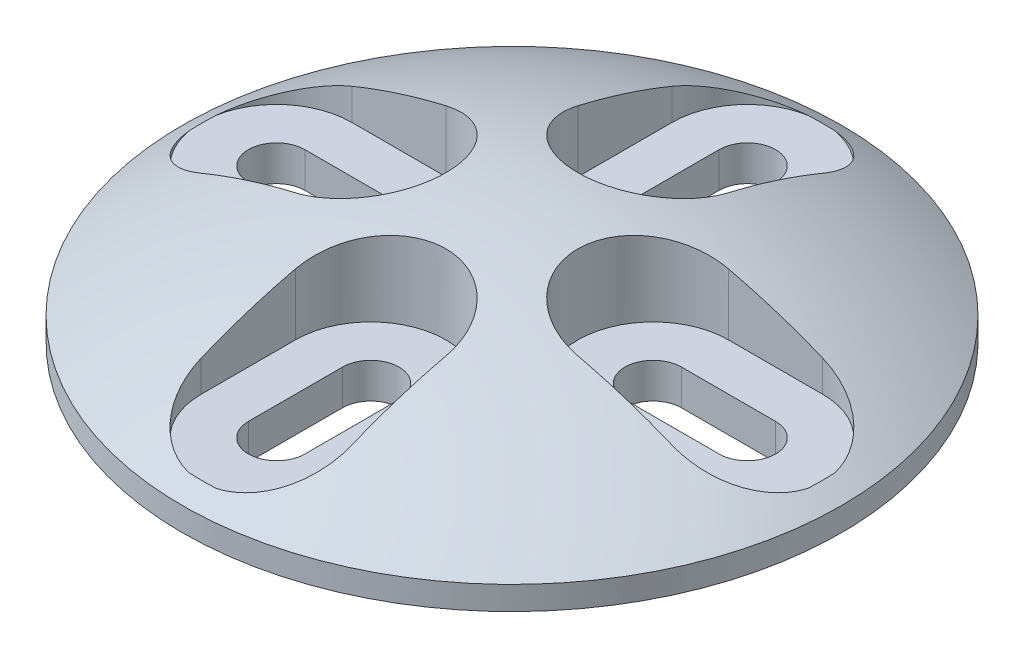
SolidWorks part; units mm, degrees
ref_plane "Front Plane" through (0, 0, 0) normal (0, 0, 1) x (1, 0, 0)
ref_plane "Top Plane" through (0, 0, 0) normal (0, 1, 0) x (1, 0, 0)
ref_plane "Right Plane" through (0, 0, 0) normal (1, 0, 0) x (0, 0, -1)
sketch "Sketch1" plane through (0, 0, 0) normal (0, 0, 1) x (1, 0, 0)
  line L0 (0, 0) -> (-14, 0)
  line L1 (0, 0) -> (0, 5)
  line L2 (-14, 0) -> (-14, 1)
  arc A0 (0, 5) -> (-14, 1) centre (0, -21.5) ccw
  dimension "D3" = 1
  dimension "D1" = 14
  dimension "D2" = 5
revolve "Revolve1" add sketch "Sketch1" angle 360 about L1
ref_plane "Plane1" through (0, 5, 0) normal (0, 1, 0) x (1, 0, 0)
sketch "Sketch2" plane through (0, 5, 0) normal (0, 1, 0) x (1, 0, 0)
  line L0 (0, 0) -> (0, -50000) construction
  line L1 (0, 0) -> (-50000, 0) construction
  line L2 (0, 10) -> (0, 6) construction
  line L3 (1.2, 10) -> (1.2, 6)
  line L4 (-1.2, 10) -> (-1.2, 6)
  line L5 (10, 0) -> (6, 0) construction
  line L6 (10, -1.2) -> (6, -1.2)
  line L7 (10, 1.2) -> (6, 1.2)
  line L8 (0, -10) -> (0, -6) construction
  line L9 (-1.2, -10) -> (-1.2, -6)
  line L10 (1.2, -10) -> (1.2, -6)
  line L11 (-10, 0) -> (-6, 0) construction
  line L12 (-10, 1.2) -> (-6, 1.2)
  line L13 (-10, -1.2) -> (-6, -1.2)
  arc A0 (1.2, 10) -> (-1.2, 10) centre (0, 10) ccw
  arc A1 (-1.2, 6) -> (1.2, 6) centre (0, 6) ccw
  arc A2 (10, -1.2) -> (10, 1.2) centre (10, 0) ccw
  arc A3 (6, 1.2) -> (6, -1.2) centre (6, 0) ccw
  arc A4 (-1.2, -10) -> (1.2, -10) centre (0, -10) ccw
  arc A5 (1.2, -6) -> (-1.2, -6) centre (0, -6) ccw
  arc A6 (-10, 1.2) -> (-10, -1.2) centre (-10, 0) ccw
  arc A7 (-6, -1.2) -> (-6, 1.2) centre (-6, 0) ccw
  point P7 (0, 8)
  point P17 (8, 0)
  point P24 (0, -8)
  point P31 (-8, 0)
  point P36 (0, 0)
  dimension "D1" = 4
  dimension "D2" = 2.4
  dimension "D3" = 8
  dimension "D4" = 4
extrude "Cut-Extrude1" cut sketch "Sketch2" against normal through all
sketch "Sketch3" plane through (0, 5, 0) normal (0, 1, 0) x (1, 0, 0)
  line L9 (10.0018, 3.1974) -> (6.0018, 3.1974)
  line L10 (6.0018, -3.2026) -> (10.0018, -3.2026)
  line L11 (3.2, 6) -> (3.2, 10)
  line L12 (-3.2, 10) -> (-3.2, 6)
  line L13 (3.2, 6) -> (3.2, 10)
  line L16 (-3.2, 10) -> (-3.2, 6)
  line L17 (3.1992, -10.0044) -> (3.1992, -6.0044)
  line L18 (-3.2008, -6.0044) -> (-3.2008, -10.0044)
  line L19 (-10.0026, -3.2018) -> (-6.0026, -3.2018)
  line L20 (-6.0026, 3.1982) -> (-10.0026, 3.1982)
  arc A7 (10.0018, -3.2026) -> (10.0018, 3.1974) centre (10.0018, -0.0026) ccw
  arc A8 (6.0018, 3.1974) -> (6.0018, -3.2026) centre (6.0018, -0.0026) ccw
  arc A9 (-3.2, 6) -> (3.2, 6) centre (0, 6) ccw
  arc A10 (3.2, 10) -> (-3.2, 10) centre (0, 10) ccw
  arc A11 (-3.2, 6) -> (3.2, 6) centre (0, 6) ccw
  arc A12 (3.2, 10) -> (-3.2, 10) centre (0, 10) ccw
  arc A13 (-3.2008, -10.0044) -> (3.1992, -10.0044) centre (-0.0008, -10.0044) ccw
  arc A16 (3.1992, -6.0044) -> (-3.2008, -6.0044) centre (-0.0008, -6.0044) ccw
  arc A17 (-10.0026, 3.1982) -> (-10.0026, -3.2018) centre (-10.0026, -0.0018) ccw
  arc A18 (-6.0026, -3.2018) -> (-6.0026, 3.1982) centre (-6.0026, -0.0018) ccw
  point P27 (-0.0004, -0.0022)
  dimension "D1" = 2
extrude "Cut-Extrude2" cut sketch "Sketch3" against normal blind 3.5
